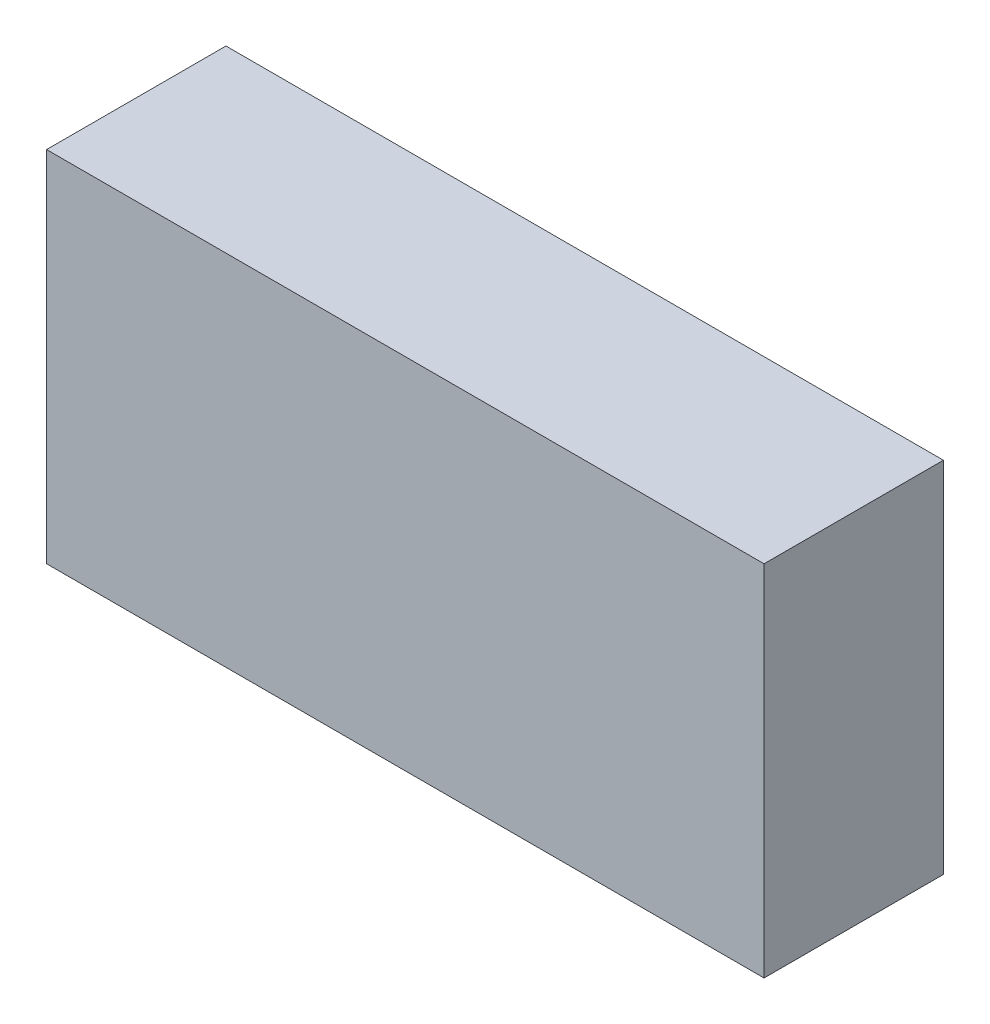
SolidWorks part; units mm, degrees
ref_plane "Front Plane" through (0, 0, 0) normal (0, 0, 1) x (1, 0, 0)
ref_plane "Top Plane" through (0, 0, 0) normal (0, 1, 0) x (1, 0, 0)
ref_plane "Right Plane" through (0, 0, 0) normal (1, 0, 0) x (0, 0, -1)
sketch "Sketch1" plane through (0, 0, 0) normal (0, 0, 1) x (1, 0, 0)
  line L0 (-20, -10) -> (20, -10)
  line L1 (20, -10) -> (20, 10)
  line L2 (20, 10) -> (-20, 10)
  line L3 (-20, 10) -> (-20, -10)
  dimension "D1" = 40
  dimension "D2" = 20
extrude "Boss-Extrude1" add sketch "Sketch1" along normal blind 10
sketch "Sketch2" plane through (0, 0, 0) normal (0, 0, 1) x (1, 0, 0)
  line L0 (-18, -5) -> (-12, -5)
  line L1 (-12, -5) -> (-12, 1)
  line L2 (-12, 1) -> (-18, 1)
  line L3 (-18, 1) -> (-18, -5)
  dimension "D1" = 6
  dimension "D2" = 6
extrude "Boss-Extrude2" add sketch "Sketch2" along normal blind 5
sketch "Sketch3" plane through (0, 0, 0) normal (0, 0, 1) x (1, 0, 0)
  line L0 (-9, -5) -> (-3, -5)
  line L1 (-3, -5) -> (-3, 1)
  line L2 (-3, 1) -> (-9, 1)
  line L3 (-9, 1) -> (-9, -5)
  dimension "D1" = 6
  dimension "D2" = 6
extrude "Boss-Extrude3" add sketch "Sketch3" along normal blind 6
